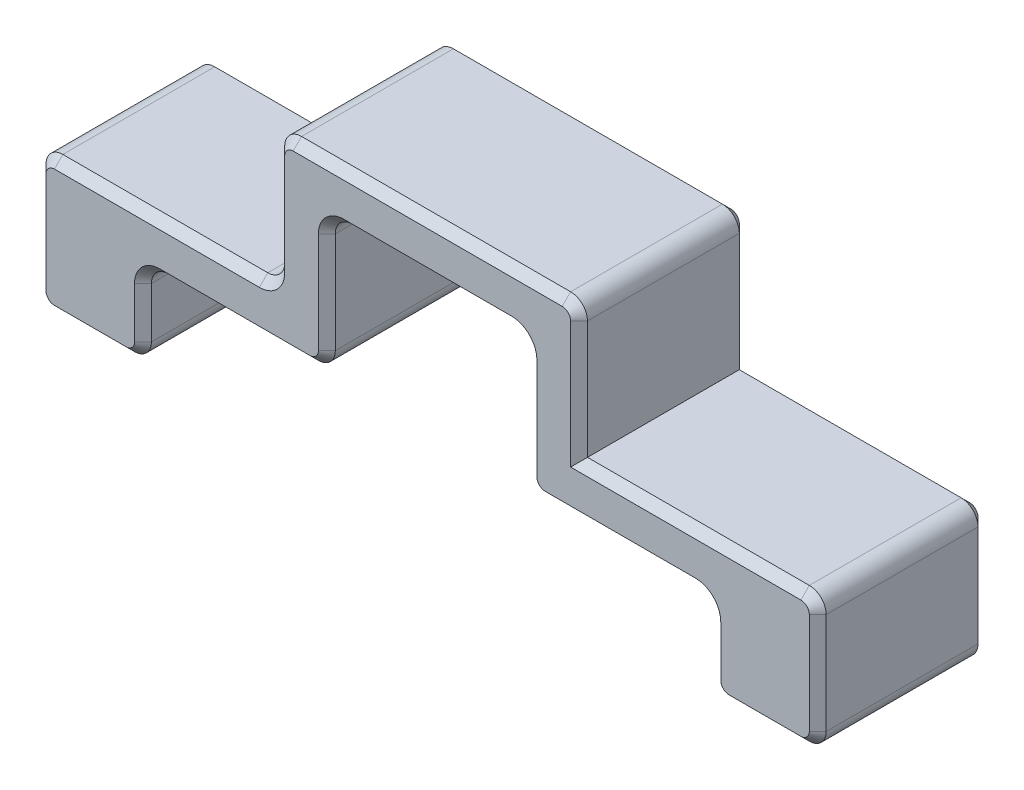
SolidWorks part; units mm, degrees
ref_plane "Front Plane" through (0, 0, 0) normal (0, 0, 1) x (1, 0, 0)
ref_plane "Top Plane" through (0, 0, 0) normal (0, 1, 0) x (1, 0, 0)
ref_plane "Right Plane" through (0, 0, 0) normal (1, 0, 0) x (0, 0, -1)
sketch "Sketch1" plane through (0, 0, 0) normal (0, 0, 1) x (1, 0, 0)
  line L0 (0, 12.3079) -> (0, -9.7673) construction
  line L1 (-24.1574, 0) -> (21.3399, 0) construction
  line L2 (-20, 16.5825) -> (-20, -11.2312) construction
  line L3 (20, 16.5825) -> (20, -11.2312) construction
  line L4 (-5.975, 0) -> (-5.975, 8)
  line L5 (-5.975, 8) -> (5.975, 8)
  line L6 (5.975, 0) -> (5.975, 8)
  line L7 (-23.125, 0) -> (-23.125, -5)
  line L8 (-23.125, -5) -> (-16.875, -5)
  line L9 (-16.875, 0) -> (-16.875, -5)
  line L10 (-5.975, 0) -> (-16.875, 0)
  line L11 (-23.125, 0) -> (-23.125, 3)
  line L12 (-23.125, 3) -> (-8.975, 3)
  line L13 (-8.975, 3) -> (-8.975, 11)
  line L14 (-8.975, 11) -> (8.975, 11)
  line L15 (8.975, 3) -> (8.975, 11)
  line L16 (5.975, 0) -> (16.875, 0)
  line L17 (23.125, 3) -> (8.975, 3)
  line L18 (23.125, 0) -> (23.125, 3)
  line L19 (23.125, 0) -> (23.125, -5)
  line L20 (16.875, 0) -> (16.875, -5)
  line L21 (23.125, -5) -> (16.875, -5)
  point P13 (0, 8)
  point P19 (-20, -5)
  point P24 (0, 11)
  dimension "D1" = 20
  dimension "D2" = 11.95
  dimension "D3" = 8
  dimension "D4" = 6.25
  dimension "D5" = 5
  dimension "D6" = 3
  dimension "D7" = 3
  dimension "D8" = 3
extrude "Boss-Extrude1" add sketch "Sketch1" along normal blind 10
fillet "Fillet1" radius 1 15 edges at (23.125, 3, 5) (23.125, -5, 5) (16.875, -5, 5) (16.875, 0, 5) (5.975, 0, 5) (-5.975, 0, 5) (-5.975, 8, 5) (5.975, 8, 5) (8.975, 11, 5) (-8.975, 11, 5) (-8.975, 3, 5) (-23.125, 3, 5) (-16.875, -5, 5) (-23.125, -5, 5) (-16.875, 0, 5)
chamfer "Chamfer1" distance 0.5 angle 45 62 edges at (8.975, 6.5, 0) (8.6821, 10.7071, 0) (0, 11, 0) (-8.6821, 10.7071, 0) (-8.975, 7, 0) (-9.2679, 3.2929, 0) (-16.05, 3, 0) (-22.8321, 2.7071, 0) (-23.125, -1, 0) (-22.8321, -4.7071, 0) (-20, -5, 0) (-17.1679, -4.7071, 0) (-16.875, -2.5, 0) (-16.5821, -0.2929, 0) (-11.425, 0, 0) (-6.2679, 0.2929, 0) (-5.975, 4, 0) (-5.6821, 7.7071, 0) (0, 8, 0) (5.6821, 7.7071, 0) (5.975, 4, 0) (6.2679, 0.2929, 0) (11.425, 0, 0) (16.5821, -0.2929, 0) (16.875, -2.5, 0) (17.1679, -4.7071, 0) (20, -5, 0) (22.8321, -4.7071, 0) (23.125, -1, 0) (22.8321, 2.7071, 0) (15.55, 3, 0) (22.8321, -4.7071, 10) (20, -5, 10) (17.1679, -4.7071, 10) (16.875, -2.5, 10) (16.5821, -0.2929, 10) (11.425, 0, 10) (6.2679, 0.2929, 10) (5.975, 4, 10) (5.6821, 7.7071, 10) (0, 8, 10) (-5.6821, 7.7071, 10) (-5.975, 4, 10) (-6.2679, 0.2929, 10) (-11.425, 0, 10) (-16.5821, -0.2929, 10) (-16.875, -2.5, 10) (-17.1679, -4.7071, 10) (-20, -5, 10) (-22.8321, -4.7071, 10) (-23.125, -1, 10) (-22.8321, 2.7071, 10) (-16.05, 3, 10) (-9.2679, 3.2929, 10) (-8.975, 7, 10) (-8.6821, 10.7071, 10) (0, 11, 10) (8.6821, 10.7071, 10) (8.975, 6.5, 10) (15.55, 3, 10) (22.8321, 2.7071, 10) (23.125, -1, 10)
